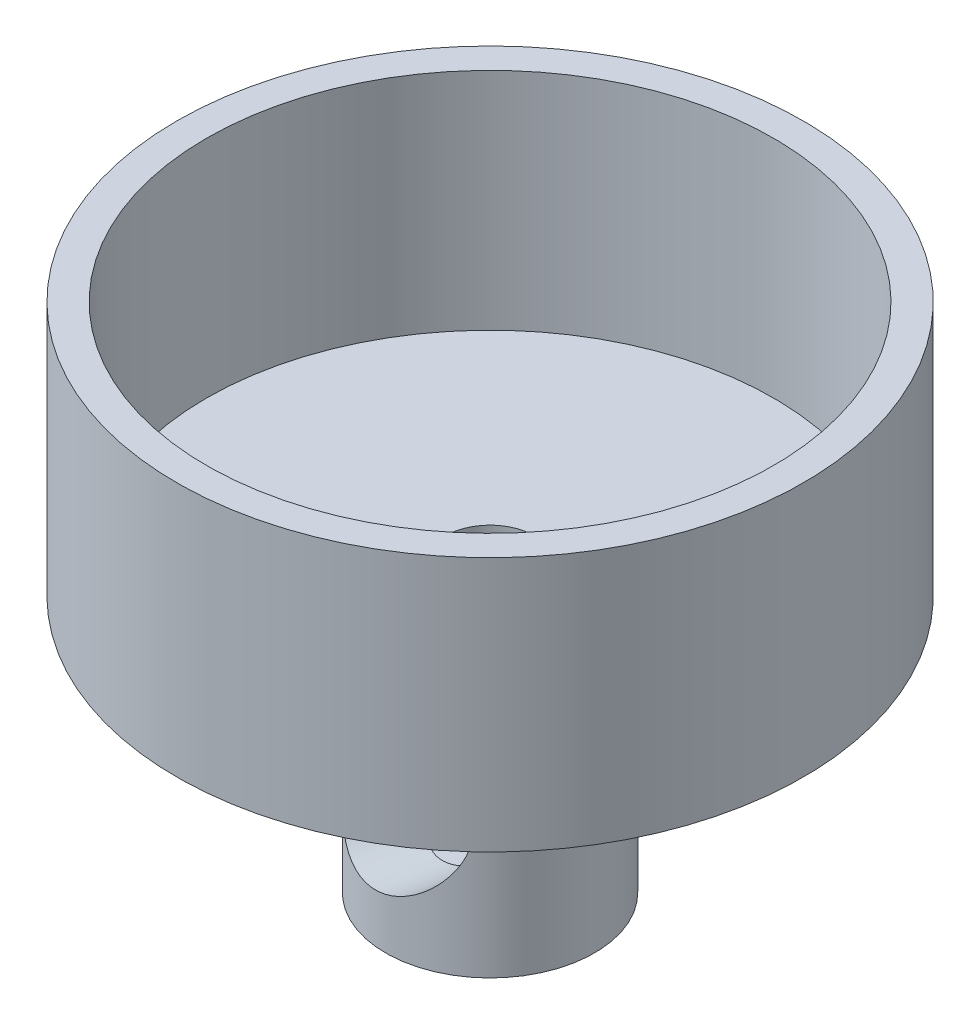
SolidWorks part; units mm, degrees
ref_plane "Plan de face" through (0, 0, 0) normal (0, 0, 1) x (1, 0, 0)
ref_plane "Plan de dessus" through (0, 0, 0) normal (0, 1, 0) x (1, 0, 0)
ref_plane "Plan de droite" through (0, 0, 0) normal (1, 0, 0) x (0, 0, -1)
sketch "Esquisse2" plane through (0, 0, 0) normal (0, 0, 1) x (1, 0, 0)
  line L0 (0, 8.5238) -> (0, -33.4388) construction
  line L1 (-19, 19.8357) -> (-19, 4.7548)
  line L2 (-19, 4.7548) -> (-3, 4.7548)
  line L3 (-3, 4.7548) -> (-3, 3.2894)
  line L4 (-9.3002, 2.7548) -> (-7, 2.7548)
  line L5 (-9.3002, 2.7548) -> (-21, 2.7548)
  line L6 (-21, 2.7548) -> (-21, 19.8357)
  line L7 (-21, 19.8357) -> (-19, 19.8357)
  line L8 (-7, 2.7548) -> (-7, -14.4575)
  line L9 (-7, -14.4575) -> (-4.7449, -14.4575)
  line L10 (-4.7449, -14.4575) -> (0, -14.4575)
  line L11 (0, -14.4575) -> (0, -12.4575)
  line L12 (0, -12.4575) -> (-3, -12.4575)
  line L13 (-3, -12.4575) -> (-3, 3.2894)
  point P5 (-1.5, -12.4575)
  point P17 (-2.3725, -14.4575)
  dimension "D3" = 7
  dimension "D1" = 2
  dimension "D2" = 2
  dimension "D4" = 3
  dimension "D5" = 2
  dimension "D6" = 19
revolve "Révolution1" add sketch "Esquisse2" angle 360 about L0
hole_wizard "Trou taraudé G1/161" positions "Esquisse3D2" profile "Esquisse5" tap size "G1/16" standard "ISO" end condition through all
sketch3d "Esquisse3D2"
  point P0 (1.2407, -5.9541, -6.8892)
  point P1 (0, 0, 0)
  point P2 (1.2407, -5.9541, -6.8892)
sketch "Esquisse5" plane through (1.2407, -5.9541, -6.8892) normal (0, 1, 0) x (-0.9842, 0, -0.1772)
  line L0 (0, 0) -> (0, 31.3896)
  line L1 (0, 31.3896) -> (5.25, 31.3896)
  line L2 (5.25, 31.3896) -> (5.25, 0)
  line L5 (5.25, 0) -> (0, 0)
  line L11 (0, -6.35) -> (0, 107.95) construction
  dimension "Diamètre du trou pour taraudage jusqu'au prochain" = 10.5
  dimension "Profondeur du trou pour taraudage jusqu'au prochain" = 31.3896
cosmetic thread "Filetage de perçage1" parameters "D2"=11
